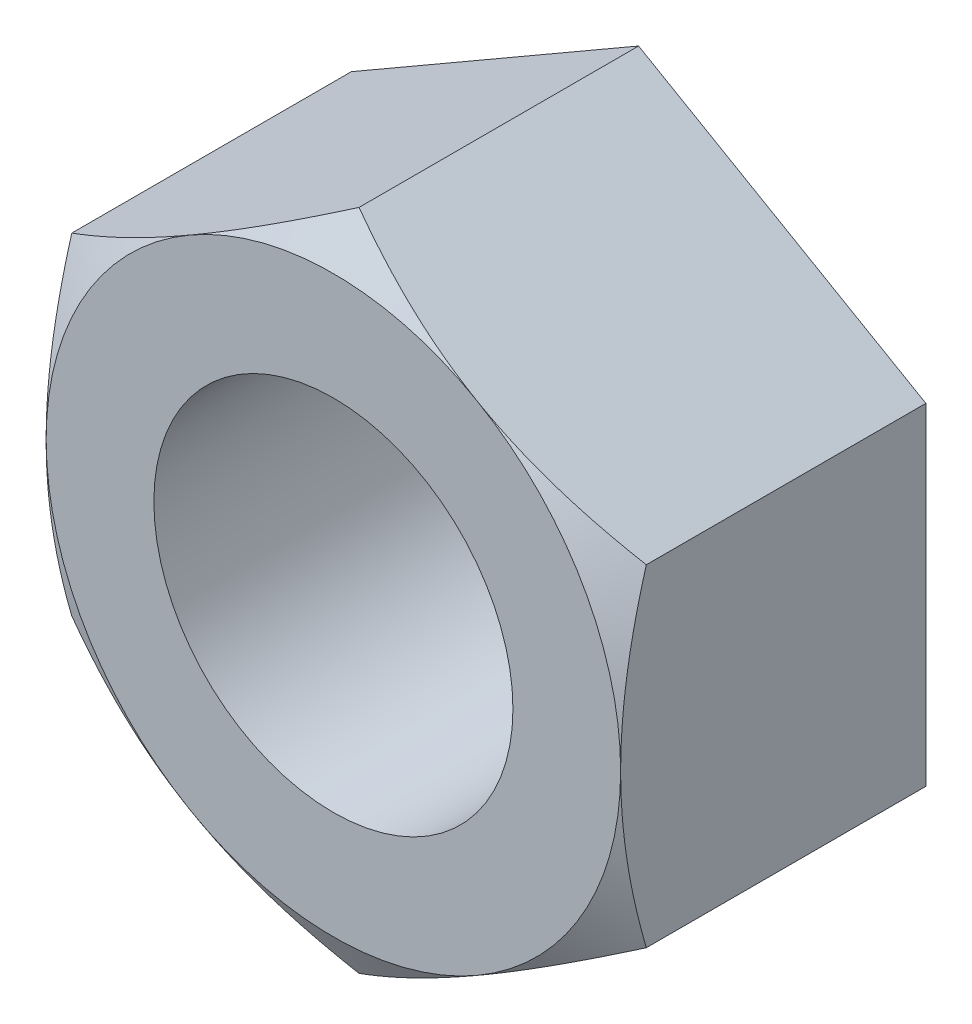
SolidWorks part; units mm, degrees
ref_plane "Front" through (0, 0, 0) normal (0, 0, 1) x (1, 0, 0)
ref_plane "Top" through (0, 0, 0) normal (0, 1, 0) x (1, 0, 0)
ref_plane "Right" through (0, 0, 0) normal (1, 0, 0) x (0, 0, -1)
sketch "Sketch1" plane through (0, 0, 0) normal (0, 0, 1) x (1, 0, 0)
  line L1 (-6.35, 3.6662) -> (-6.35, -3.6662)
  line L2 (-6.35, -3.6662) -> (0, -7.3323)
  line L3 (0, -7.3323) -> (6.35, -3.6662)
  line L4 (6.35, -3.6662) -> (6.35, 3.6662)
  line L5 (6.35, 3.6662) -> (0, 7.3323)
  line L6 (0, 7.3323) -> (-6.35, 3.6662)
  circle A0 centre (0, 0) radius 6.35 construction
  circle A1 centre (0, 0) radius 3.9688
  point P10 (0, 3.9688)
  dimension "hex" = 12.7
  dimension "dia" = 7.9375
extrude "Extrude1" add sketch "Sketch1" along normal mid plane 6.7469
sketch "Sketch7" plane through (0, 0, 3.3734) normal (0, 0, 1) x (1, 0, 0)
  circle A0 centre (0, 0) radius 6.35 construction
  circle A1 centre (0, 0) radius 6.35
extrude "Extrude2" cut sketch "Sketch7" against normal blind 25.4 draft 60 flip side to cut
